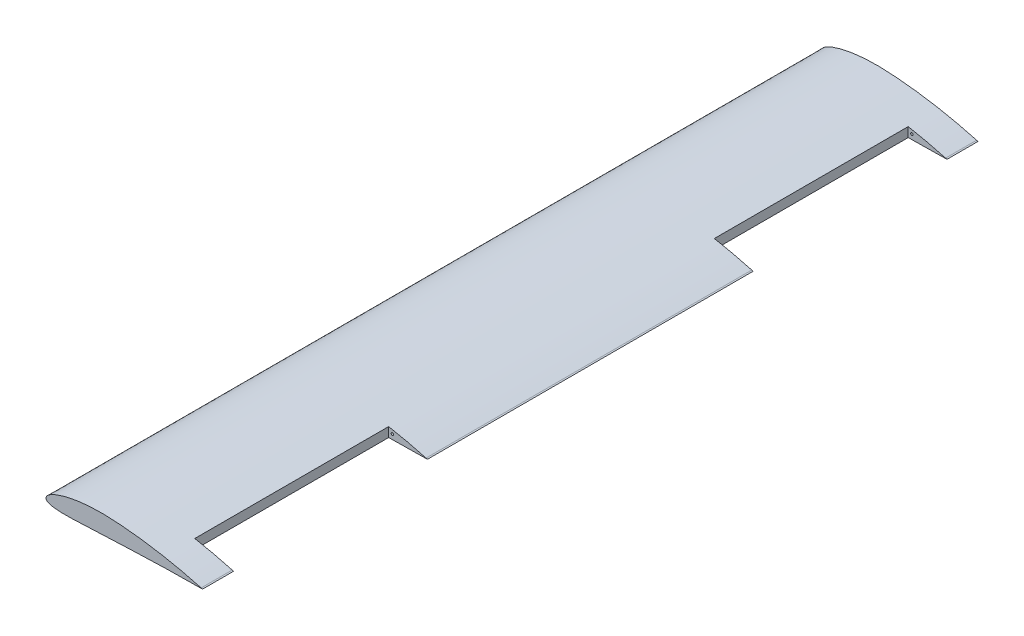
SolidWorks part; units mm, degrees
ref_plane "Front Plane" through (0, 0, 0) normal (0, 0, 1) x (1, 0, 0)
ref_plane "Top Plane" through (0, 0, 0) normal (0, 1, 0) x (1, 0, 0)
ref_plane "Right Plane" through (0, 0, 0) normal (1, 0, 0) x (0, 0, -1)
curve "Curve1"
  spline degree 3 poles (250.0418, 0.3123, 0) (249.961, 0.3347, 0) (249.6384, 0.4243, 0) (248.9136, 0.6242, 0) (247.7088, 0.9559, 0) (246.0275, 1.4135, 0) (243.876, 1.9928, 0) (241.2616, 2.6864, 0) (238.1937, 3.486, 0) (234.6829, 4.3823, 0) (230.7419, 5.3652, 0) (226.3847, 6.4232, 0) (221.6274, 7.545, 0) (216.487, 8.7177, 0) (210.9829, 9.9301, 0) (205.135, 11.1676, 0) (198.9658, 12.4195, 0) (192.4982, 13.6713, 0) (185.757, 14.9108, 0) (178.7682, 16.1267, 0) (171.5585, 17.3048, 0) (164.1562, 18.435, 0) (156.59, 19.5049, 0) (148.8901, 20.5039, 0) (141.0869, 21.4209, 0) (133.2116, 22.2468, 0) (125.296, 22.9721, 0) (117.3722, 23.5888, 0) (109.4726, 24.0876, 0) (101.5972, 24.4704, 0) (93.7681, 24.7066, 0) (86.018, 24.7356, 0) (78.4147, 24.5703, 0) (71.0008, 24.2125, 0) (63.8099, 23.6677, 0) (56.8744, 22.9461, 0) (50.2257, 22.0584, 0) (43.8933, 21.0182, 0) (37.9051, 19.8404, 0) (32.2871, 18.5422, 0) (27.063, 17.1418, 0) (22.2542, 15.6583, 0) (17.8798, 14.1108, 0) (13.9559, 12.5196, 0) (10.4963, 10.9032, 0) (7.5119, 9.2797, 0) (5.0106, 7.6653, 0) (2.9966, 6.0735, 0) (1.471, 4.5122, 0) (0.4338, 2.9806, 0) (-0.101, 1.4638, 0) (-0.0878, -0.0176, 0) (0.469, -1.3889, 0) (1.5356, -2.5849, 0) (3.0572, -3.612, 0) (5.0232, -4.4955, 0) (7.4294, -5.2476, 0) (10.2696, -5.873, 0) (13.5333, -6.3761, 0) (17.2073, -6.7609, 0) (21.2768, -7.0324, 0) (25.7251, -7.1978, 0) (30.5348, -7.2628, 0) (35.6873, -7.2375, 0) (41.1636, -7.13, 0) (46.9437, -6.9515, 0) (53.0075, -6.713, 0) (59.3339, -6.4274, 0) (65.9015, -6.1067, 0) (72.6882, -5.7642, 0) (79.6715, -5.4134, 0) (86.8279, -5.0678, 0) (94.142, -4.7369, 0) (101.6219, -4.4457, 0) (109.2388, -4.1491, 0) (116.9549, -3.8319, 0) (124.7086, -3.5092, 0) (132.4705, -3.1872, 0) (140.2106, -2.8713, 0) (147.8992, -2.5674, 0) (155.5063, -2.2796, 0) (163.0022, -2.011, 0) (170.3573, -1.7645, 0) (177.5423, -1.5405, 0) (184.5286, -1.3405, 0) (191.2879, -1.1638, 0) (197.7928, -1.0102, 0) (204.0166, -0.8774, 0) (209.9338, -0.7653, 0) (215.5199, -0.6707, 0) (220.7516, -0.592, 0) (225.607, -0.5278, 0) (230.0656, -0.4753, 0) (234.1082, -0.4333, 0) (237.7177, -0.3994, 0) (240.8783, -0.3733, 0) (243.5765, -0.3532, 0) (245.8005, -0.3376, 0) (247.5405, -0.3264, 0) (248.7889, -0.3188, 0) (249.5401, -0.3148, 0) (249.8746, -0.3128, 0) (249.9582, -0.3123, 0) knots 0 0 0 0 0.000491 0.001962 0.004406 0.007815 0.012174 0.017465 0.023667 0.030754 0.0387 0.04747 0.057032 0.067345 0.07837 0.090062 0.102376 0.115262 0.128669 0.142545 0.156835 0.171482 0.186429 0.201617 0.216985 0.232474 0.248023 0.263569 0.279051 0.29441 0.309776 0.324951 0.339825 0.354342 0.368446 0.382083 0.395202 0.407751 0.419686 0.430962 0.441537 0.451377 0.460447 0.468723 0.476183 0.482815 0.488619 0.49361 0.49783 0.501365 0.504372 0.507113 0.509853 0.512855 0.516368 0.52054 0.525445 0.531118 0.537568 0.544788 0.552762 0.561466 0.570873 0.58095 0.591662 0.602972 0.614841 0.627227 0.640086 0.653377 0.667052 0.681064 0.695367 0.70996 0.724934 0.74004 0.75522 0.770415 0.785568 0.800619 0.81551 0.830182 0.844577 0.858639 0.872311 0.885538 0.898266 0.910444 0.922022 0.932951 0.943187 0.952686 0.961409 0.969318 0.97638 0.982563 0.987842 0.992193 0.995598 0.99804 0.99951 1 1 1 1
sketch "Sketch1" plane through (0, 0, 0) normal (0, 0, 1) x (1, 0, 0)
  line L0 (250.0418, 0.3123) -> (252.266, -0.3123)
  line L1 (249.9582, -0.3123) -> (252.266, -0.3123)
  spline S0 degree 3 poles (874.6474, 1899.2322) (309.5698, -21.7073) (280.1632, -7.9964) (248.9136, 0.6242) (247.7088, 0.9559) (246.0275, 1.4135) (242.8541, 2.2679) (239.0684, 3.2627) (234.6829, 4.3823) (230.7419, 5.3652) (226.3847, 6.4232) (221.6274, 7.545) (216.487, 8.7177) (210.9829, 9.9301) (205.135, 11.1676) (198.9658, 12.4195) (192.4982, 13.6713) (185.757, 14.9108) (178.7682, 16.1267) (171.5585, 17.3048) (164.1562, 18.435) (156.59, 19.5049) (148.8901, 20.5039) (141.0869, 21.4209) (133.2116, 22.2468) (125.296, 22.9721) (117.3722, 23.5888) (109.4726, 24.0876) (101.5972, 24.4704) (93.7681, 24.7066) (86.018, 24.7356) (78.4147, 24.5703) (71.0008, 24.2125) (63.8099, 23.6677) (56.8744, 22.9461) (50.2257, 22.0584) (43.8933, 21.0182) (37.9051, 19.8404) (32.2871, 18.5422) (27.063, 17.1418) (22.2542, 15.6583) (17.8798, 14.1108) (13.9559, 12.5196) (10.4963, 10.9032) (7.5119, 9.2797) (5.0106, 7.6653) (2.9966, 6.0735) (1.471, 4.5122) (0.4338, 2.9806) (-0.101, 1.4638) (-0.0878, -0.0176) (0.469, -1.3889) (1.5356, -2.5849) (3.0572, -3.612) (5.0232, -4.4955) (7.4294, -5.2476) (10.2696, -5.873) (13.5333, -6.3761) (17.2073, -6.7609) (21.2768, -7.0324) (25.7251, -7.1978) (30.5348, -7.2628) (35.6873, -7.2375) (41.1636, -7.13) (46.9437, -6.9515) (53.0075, -6.713) (59.3339, -6.4274) (65.9015, -6.1067) (72.6882, -5.7642) (79.6715, -5.4134) (86.8279, -5.0678) (94.142, -4.7369) (101.6219, -4.4457) (109.2388, -4.1491) (116.9549, -3.8319) (124.7086, -3.5092) (132.4705, -3.1872) (140.2106, -2.8713) (147.8992, -2.5674) (155.5063, -2.2796) (163.0022, -2.011) (170.3573, -1.7645) (177.5423, -1.5405) (184.5286, -1.3405) (191.2879, -1.1638) (197.7928, -1.0102) (204.0166, -0.8774) (209.9338, -0.7653) (215.5199, -0.6707) (220.7516, -0.592) (225.607, -0.5278) (230.0656, -0.4753) (234.1082, -0.4333) (237.7177, -0.3994) (240.8783, -0.3733) (243.5765, -0.3532) (245.8005, -0.3376) (247.5405, -0.3264) (248.7889, -0.3188) (294.3095, -0.0727) (339.3915, 3.9527) (395.8311, -1993.1242) knots -0.185575 -0.185575 -0.185575 -0.185575 0.000491 0.001962 0.004406 0.007815 0.012174 0.023667 0.030754 0.0387 0.04747 0.057032 0.067345 0.07837 0.090062 0.102376 0.115262 0.128669 0.142545 0.156835 0.171482 0.186429 0.201617 0.216985 0.232474 0.248023 0.263569 0.279051 0.29441 0.309776 0.324951 0.339825 0.354342 0.368446 0.382083 0.395202 0.407751 0.419686 0.430962 0.441537 0.451377 0.460447 0.468723 0.476183 0.482815 0.488619 0.49361 0.49783 0.501365 0.504372 0.507113 0.509853 0.512855 0.516368 0.52054 0.525445 0.531118 0.537568 0.544788 0.552762 0.561466 0.570873 0.58095 0.591662 0.602972 0.614841 0.627227 0.640086 0.653377 0.667052 0.681064 0.695367 0.70996 0.724934 0.74004 0.75522 0.770415 0.785568 0.800619 0.81551 0.830182 0.844577 0.858639 0.872311 0.885538 0.898266 0.910444 0.922022 0.932951 0.943187 0.952686 0.961409 0.969318 0.97638 0.982563 0.987842 0.992193 0.995598 0.99804 0.99951 1.262379 1.262379 1.262379 1.262379 only from (250.0418, 0.3123) to (249.9582, -0.3123) construction
  spline S1 degree 3 poles (250.0418, 0.3123) (249.961, 0.3347) (249.6384, 0.4243) (248.9136, 0.6242) (247.7088, 0.9559) (246.0275, 1.4135) (242.8541, 2.2679) (239.0684, 3.2627) (234.6829, 4.3823) (230.7419, 5.3652) (226.3847, 6.4232) (221.6274, 7.545) (216.487, 8.7177) (210.9829, 9.9301) (205.135, 11.1676) (198.9658, 12.4195) (192.4982, 13.6713) (185.757, 14.9108) (178.7682, 16.1267) (171.5585, 17.3048) (164.1562, 18.435) (156.59, 19.5049) (148.8901, 20.5039) (141.0869, 21.4209) (133.2116, 22.2468) (125.296, 22.9721) (117.3722, 23.5888) (109.4726, 24.0876) (101.5972, 24.4704) (93.7681, 24.7066) (86.018, 24.7356) (78.4147, 24.5703) (71.0008, 24.2125) (63.8099, 23.6677) (56.8744, 22.9461) (50.2257, 22.0584) (43.8933, 21.0182) (37.9051, 19.8404) (32.2871, 18.5422) (27.063, 17.1418) (22.2542, 15.6583) (17.8798, 14.1108) (13.9559, 12.5196) (10.4963, 10.9032) (7.5119, 9.2797) (5.0106, 7.6653) (2.9966, 6.0735) (1.471, 4.5122) (0.4338, 2.9806) (-0.101, 1.4638) (-0.0878, -0.0176) (0.469, -1.3889) (1.5356, -2.5849) (3.0572, -3.612) (5.0232, -4.4955) (7.4294, -5.2476) (10.2696, -5.873) (13.5333, -6.3761) (17.2073, -6.7609) (21.2768, -7.0324) (25.7251, -7.1978) (30.5348, -7.2628) (35.6873, -7.2375) (41.1636, -7.13) (46.9437, -6.9515) (53.0075, -6.713) (59.3339, -6.4274) (65.9015, -6.1067) (72.6882, -5.7642) (79.6715, -5.4134) (86.8279, -5.0678) (94.142, -4.7369) (101.6219, -4.4457) (109.2388, -4.1491) (116.9549, -3.8319) (124.7086, -3.5092) (132.4705, -3.1872) (140.2106, -2.8713) (147.8992, -2.5674) (155.5063, -2.2796) (163.0022, -2.011) (170.3573, -1.7645) (177.5423, -1.5405) (184.5286, -1.3405) (191.2879, -1.1638) (197.7928, -1.0102) (204.0166, -0.8774) (209.9338, -0.7653) (215.5199, -0.6707) (220.7516, -0.592) (225.607, -0.5278) (230.0656, -0.4753) (234.1082, -0.4333) (237.7177, -0.3994) (240.8783, -0.3733) (243.5765, -0.3532) (245.8005, -0.3376) (247.5405, -0.3264) (248.7889, -0.3188) (249.5401, -0.3148) (249.8746, -0.3128) (249.9582, -0.3123) knots 0 0 0 0 0.000491 0.001962 0.004406 0.007815 0.012174 0.023667 0.030754 0.0387 0.04747 0.057032 0.067345 0.07837 0.090062 0.102376 0.115262 0.128669 0.142545 0.156835 0.171482 0.186429 0.201617 0.216985 0.232474 0.248023 0.263569 0.279051 0.29441 0.309776 0.324951 0.339825 0.354342 0.368446 0.382083 0.395202 0.407751 0.419686 0.430962 0.441537 0.451377 0.460447 0.468723 0.476183 0.482815 0.488619 0.49361 0.49783 0.501365 0.504372 0.507113 0.509853 0.512855 0.516368 0.52054 0.525445 0.531118 0.537568 0.544788 0.552762 0.561466 0.570873 0.58095 0.591662 0.602972 0.614841 0.627227 0.640086 0.653377 0.667052 0.681064 0.695367 0.70996 0.724934 0.74004 0.75522 0.770415 0.785568 0.800619 0.81551 0.830182 0.844577 0.858639 0.872311 0.885538 0.898266 0.910444 0.922022 0.932951 0.943187 0.952686 0.961409 0.969318 0.97638 0.982563 0.987842 0.992193 0.995598 0.99804 0.99951 1 1 1 1
  dimension "D1" = 252.266
extrude "Boss-Extrude1" add sketch "Sketch1" along normal mid plane 1250
sketch "Sketch2" plane through (0, 0, 0) normal (0, 1, 0) x (1, 0, 0)
  line L0 (252.266, -625) -> (252.266, 625) construction
  line L1 (252.266, -575) -> (189.766, -575)
  line L2 (252.266, -575) -> (252.266, -262.5)
  line L3 (252.266, -262.5) -> (189.766, -262.5)
  line L4 (189.766, -575) -> (189.766, -262.5)
  line L5 (-0.074, -625) -> (250.0418, -625) construction
  dimension "D1" = 312.5
  dimension "D2" = 62.5
  dimension "D3" = 50
extrude "Cut-Extrude1" cut sketch "Sketch2" against normal through all both and the other way through all
sketch "Sketch3" plane through (0, 0, 262.5) normal (0, 0, 1) x (1, 0, 0)
  line L0 (189.766, -1.2049) -> (189.766, 14.1707) construction
  circle A0 centre (195.766, 6.6877) radius 2
  dimension "D2" = 4
  dimension "D3" = 7
  dimension "D1" = 6
extrude "Cut-Extrude2" cut sketch "Sketch3" against normal blind 30
sketch "Sketch4" plane through (0, 0, 575) normal (0, 0, -1) x (-1, 0, 0)
  circle A0 centre (-195.766, 6.6877) radius 2 construction
  circle A1 centre (-195.766, 6.6877) radius 2
extrude "Cut-Extrude3" cut sketch "Sketch4" against normal blind 30
mirror "Mirror1" about plane through (0, 0, 0) normal (0, 0, 1) of "Cut-Extrude1", "Cut-Extrude2", "Cut-Extrude3"
